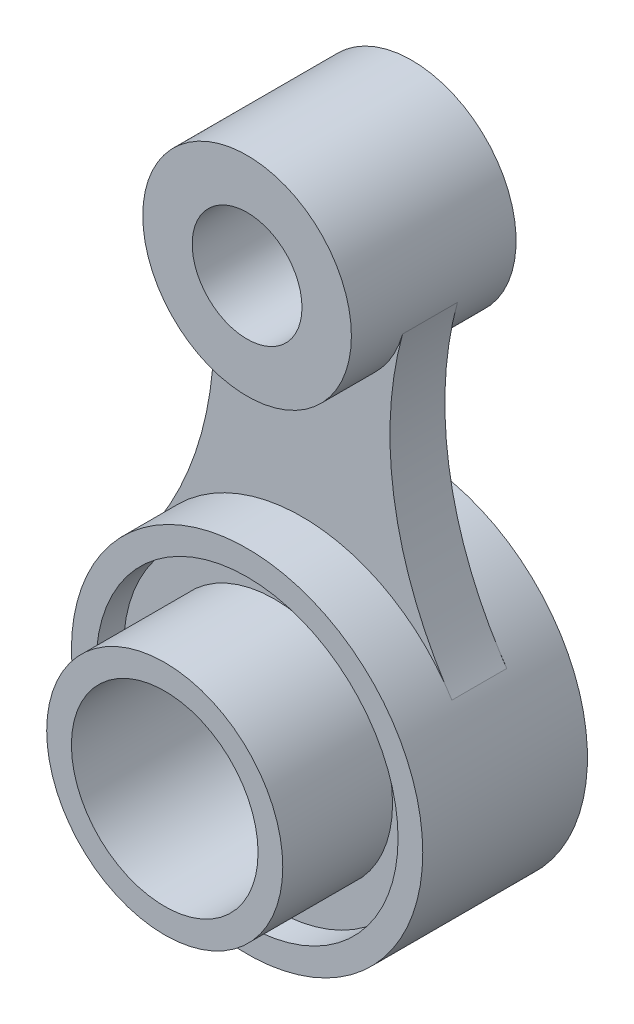
SolidWorks part; units mm, degrees
ref_plane "Plan de face" through (0, 0, 0) normal (0, 0, 1) x (1, 0, 0)
ref_plane "Plan de dessus" through (0, 0, 0) normal (0, 1, 0) x (1, 0, 0)
ref_plane "Plan de droite" through (0, 0, 0) normal (1, 0, 0) x (0, 0, -1)
sketch "Esquisse3" plane through (0, 0, 0) normal (0, 0, 1) x (1, 0, 0)
  line L0 (0, 84.9798) -> (0, -113.1048) construction
  circle A0 centre (0, 0) radius 19
  circle A1 centre (0, -75) radius 32
  arc A2 (18.3188, -5.0421) -> (27.297, -58.3005) centre (80.0241, -22.0259) ccw
  arc A3 (18.3188, -5.0421) -> (-18.3188, -5.0421) centre (0, 0) cw
  arc A4 (27.297, -58.3005) -> (-27.297, -58.3005) centre (0, -75) ccw
  arc A5 (-18.3188, -5.0421) -> (-27.297, -58.3005) centre (-80.0241, -22.0259) cw
  dimension "D2" = 19
  dimension "D3" = 32
  dimension "D4" = 64
  dimension "D1" = 75
extrude "Boss.-Extru.7" add sketch "Esquisse3" along normal blind 10
sketch "Esquisse5" plane through (0, 0, 0) normal (0, 0, -1) x (-1, 0, 0)
  circle A0 centre (0, 0) radius 19
  circle A1 centre (0, -75) radius 32
  dimension "D1" = 38
  dimension "D2" = 64
sketch "Esquisse14" plane through (0, 0, 0) normal (0, 0, -1) x (-1, 0, 0)
  circle A0 centre (0, 0) radius 19
  circle A1 centre (0, -75) radius 32
  dimension "D1" = 38
  dimension "D2" = 64
extrude "Boss.-Extru.13" add sketch "Esquisse14" along normal blind 10
sketch "Esquisse15" plane through (0, 0, 10) normal (0, 0, 1) x (1, 0, 0)
  circle A0 centre (0, 0) radius 19
  dimension "D1" = 38
extrude "Boss.-Extru.14" add sketch "Esquisse15" along normal blind 10
sketch "Esquisse16" plane through (0, 0, 10) normal (0, 0, 1) x (1, 0, 0)
  circle A0 centre (0, -75) radius 32
  dimension "D1" = 64
extrude "Boss.-Extru.16" add sketch "Esquisse16" along normal blind 10
sketch "Esquisse21" plane through (0, 0, 20) normal (0, 0, 1) x (1, 0, 0)
  circle A0 centre (0, -75) radius 27.5
  dimension "D1" = 55
extrude "Enlèv. mat.-Extru.10" cut sketch "Esquisse21" against normal blind 5
sketch "Esquisse25" plane through (0, 0, 15) normal (0, 0, 1) x (1, 0, 0)
  circle A0 centre (0, -75) radius 21.5
  dimension "D1" = 43
extrude "Boss.-Extru.18" add sketch "Esquisse25" along normal blind 20
sketch "Esquisse26" plane through (0, 0, 35) normal (0, 0, 1) x (1, 0, 0)
  circle A0 centre (0, -75) radius 17
  dimension "D1" = 34
extrude "Enlèv. mat.-Extru.11" cut sketch "Esquisse26" against normal blind 45
sketch "Esquisse27" plane through (0, 0, 20) normal (0, 0, 1) x (1, 0, 0)
  circle A0 centre (0, 0) radius 10
  dimension "D1" = 20
extrude "Enlèv. mat.-Extru.12" cut sketch "Esquisse27" against normal blind 45
